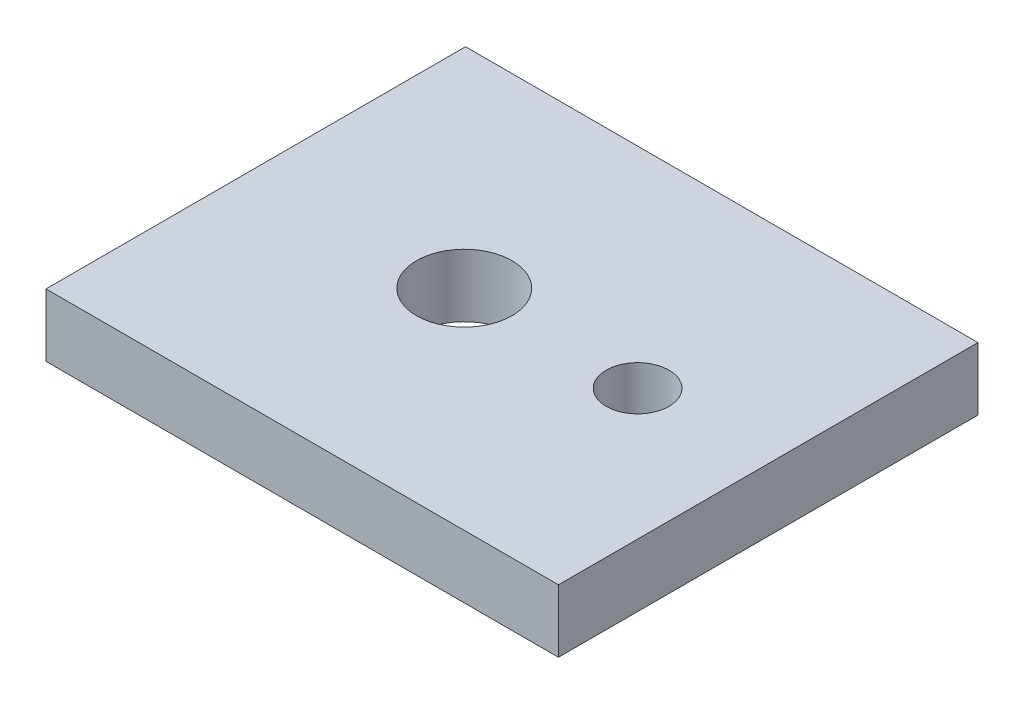
SolidWorks part; units mm, degrees
ref_plane "Front Plane" through (0, 0, 0) normal (0, 0, 1) x (1, 0, 0)
ref_plane "Top Plane" through (0, 0, 0) normal (0, 1, 0) x (1, 0, 0)
ref_plane "Right Plane" through (0, 0, 0) normal (1, 0, 0) x (0, 0, -1)
sketch "Sketch1" plane through (0, 0, 0) normal (0, 1, 0) x (1, 0, 0)
  line L1 (0, 0) -> (-51.816, 0)
  line L2 (0, 0) -> (0, 42.418)
  line L3 (0, 42.418) -> (-51.816, 42.418)
  line L4 (-51.816, 0) -> (-51.816, 42.418)
  circle A0 centre (-30.734, 21.209) radius 4.826
  circle A1 centre (-13.208, 21.209) radius 3.175
  dimension "D5" = 9.652
  dimension "D6" = 6.35
  dimension "D1" = 51.816
  dimension "D2" = 42.418
  dimension "D3" = 21.082
  dimension "D4" = 17.526
extrude "Boss-Extrude1" add sketch "Sketch1" along normal blind 6.35
equation "\"Dp_gear\"= 1"
equation "\"Dp_pinion\"= 0.375"
equation "\"OD_gear\"= 1.0417"
equation "\"OD_pinion\"= 0.4167"
equation "\"C\"= ( \"Dp_gear\" + \"Dp_pinion\" ) / 2"
equation "\"clr\"= 0.0625"
equation "\"brg_L\"= 0.25"
equation "\"wall\"= \"brg_L\""
equation "\"shaft_L\"= 1"
equation "\"cav_depth\"= \"shaft_L\" - 2 * \"brg_L\""
equation "\"cav_L\"= \"OD_gear\" / 2 + \"C\" + \"OD_pinion\" / 2 + 2 * \"clr\""
equation "\"cav_W\"= \"OD_gear\" + 2 * \"clr\""
equation "\"brg_OD_out\"= 0.375"
equation "\"brg_OD_in\" = 0.25"
